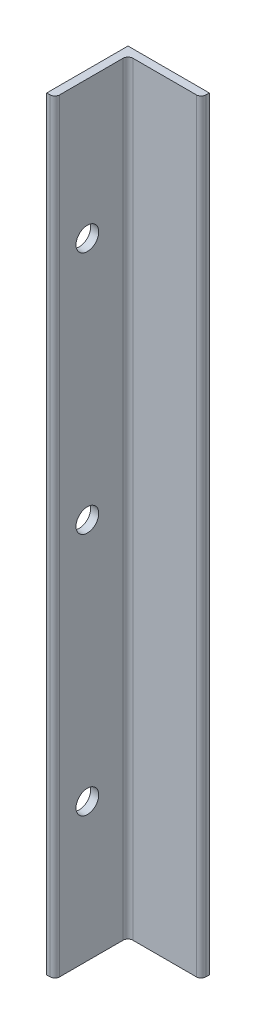
SolidWorks part; units mm, degrees
material "ASTM A36 Steel"
ref_plane "Front Plane" through (0, 0, 0) normal (0, 0, 1) x (1, 0, 0)
ref_plane "Top Plane" through (0, 0, 0) normal (0, 1, 0) x (1, 0, 0)
ref_plane "Right Plane" through (0, 0, 0) normal (1, 0, 0) x (0, 0, -1)
sketch "Sketch1" plane through (0, 0, 0) normal (0, 1, 0) x (1, 0, 0)
  line L0 (-18.4999, 39.2132) -> (-68.4999, 39.2132)
  line L1 (-68.4999, 39.2132) -> (-68.4999, -10.7868)
  line L2 (-68.4999, -10.7868) -> (-66.4999, -10.7868)
  line L3 (-63.4999, -7.7868) -> (-63.4999, 31.2132)
  line L4 (-60.4999, 34.2132) -> (-21.4999, 34.2132)
  line L5 (-18.4999, 37.2132) -> (-18.4999, 39.2132)
  arc A0 (-66.4999, -10.7868) -> (-63.4999, -7.7868) centre (-66.4999, -7.7868) ccw
  arc A1 (-63.4999, 31.2132) -> (-60.4999, 34.2132) centre (-60.4999, 31.2132) cw
  arc A2 (-21.4999, 34.2132) -> (-18.4999, 37.2132) centre (-21.4999, 37.2132) ccw
  point P8 (-63.4999, -10.7868)
  point P13 (-18.4999, 34.2132)
  dimension "D5" = 3
  dimension "D1" = 50
  dimension "D2" = 50
  dimension "D3" = 5
  dimension "D4" = 5
extrude "Boss-Extrude1" add sketch "Sketch1" along normal blind 470
sketch "Sketch2" plane through (-63.4999, 0, 0) normal (1, 0, 0) x (0, 0, -1)
  line L1 (39.2132, 470) -> (35.2132, 470)
  line L2 (39.2132, 470) -> (39.2132, 434)
  line L3 (39.2132, 434) -> (35.2132, 434)
  line L4 (35.2132, 470) -> (35.2132, 434)
  line L5 (39.2132, 470) -> (35.2132, 434) construction
  line L6 (39.2132, 434) -> (35.2132, 470) construction
  point P4 (37.2132, 452)
  dimension "D1" = 4
  dimension "D2" = 36
extrude "Cut-Extrude1" [suppressed] cut sketch "Sketch2" against normal through all both and the other way through all
sketch "Sketch3" plane through (-63.4999, 0, 0) normal (1, 0, 0) x (0, 0, -1)
  line L0 (-7.7868, 470) -> (-7.7868, 0) construction
  line L1 (-10.7868, 470) -> (-10.7868, 0) construction
  circle A0 centre (9.2132, 235) radius 7
  circle A1 centre (9.2132, 85) radius 7
  circle A2 centre (9.2132, 385) radius 7
  point P8 (-7.7868, 235)
  dimension "D1" = 14
  dimension "D2" = 14
  dimension "D3" = 14
  dimension "D4" = 150
  dimension "D5" = 150
  dimension "D6" = 0
  dimension "D7" = 20
  dimension "D8" = 20
extrude "Cut-Extrude2" cut sketch "Sketch3" against normal blind 10
